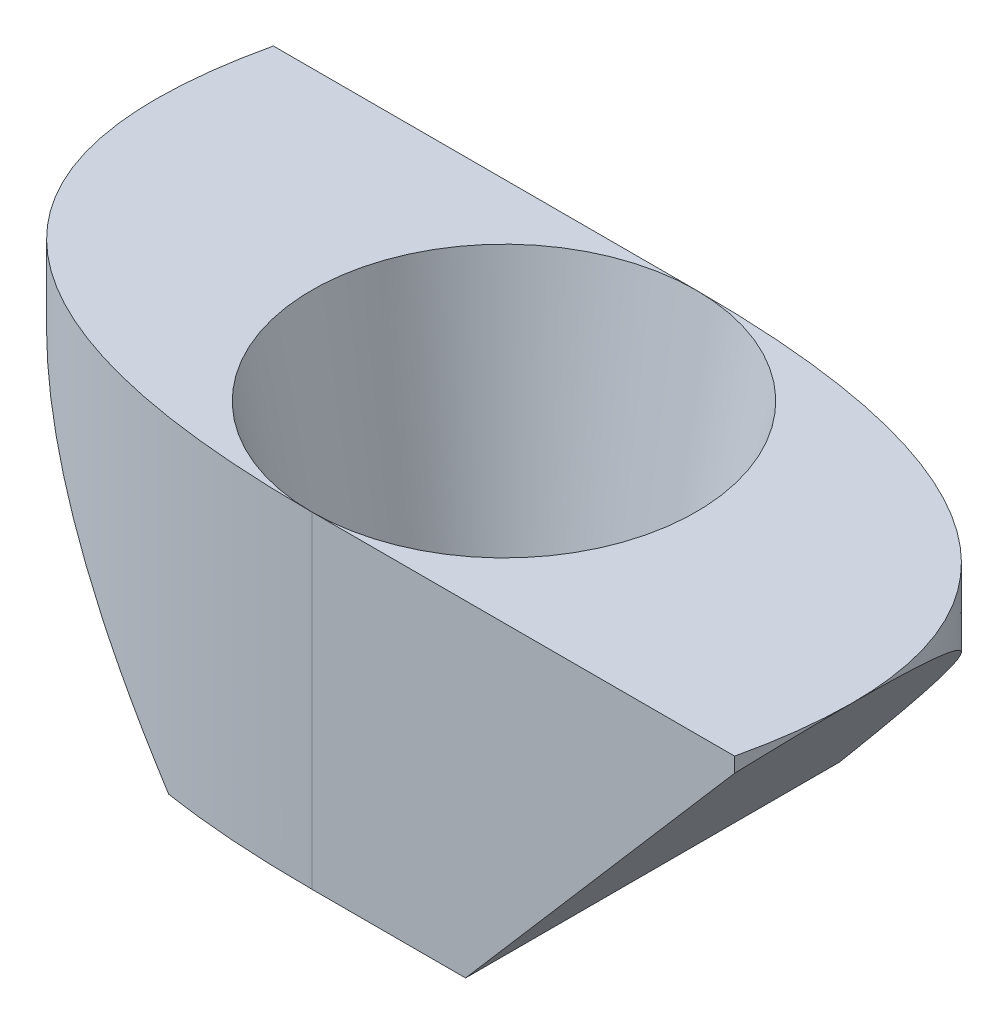
SolidWorks part; units mm, degrees
ref_plane "Front Plane" through (0, 0, 0) normal (0, 0, 1) x (1, 0, 0)
ref_plane "Top Plane" through (0, 0, 0) normal (0, 1, 0) x (1, 0, 0)
ref_plane "Right Plane" through (0, 0, 0) normal (1, 0, 0) x (0, 0, -1)
sketch "Sketch1" plane through (0, 0, 0) normal (0, 1, 0) x (1, 0, 0)
  line L0 (0, 3.175) -> (13.97, 3.175) construction
  line L1 (6.985, 0) -> (13.97, 0)
  line L3 (0, 6.35) -> (6.985, 6.35)
  line L5 (6.985, 6.35) -> (6.985, 0) construction
  spline S0 degree 2 poles (6.985, 6.35) (15.4152, 6.3545) (13.97, 0) knots 0 0 0 1 1 1
  spline S1 degree 2 poles (6.985, 0) (-1.4452, -0.0045) (0, 6.35) knots 0 0 0 1 1 1
  point P0 (6.985, 3.175)
extrude "Boss-Extrude2" add sketch "Sketch1" along normal blind 7.62 contours L3 S0 L1 S1
sketch "Sketch3" plane through (0, 0, 0) normal (0, 0, 1) x (1, 0, 0)
  line L1 (-0.2115, 7.62) -> (-0.2115, 0) construction
  line L3 (6.985, 7.62) -> (-0.2115, 7.62) construction
  line L4 (-0.2115, 7.62) -> (3.81, 7.62)
  line L9 (-0.2115, 7.62) -> (-0.2115, 5.461)
  line L10 (-0.2115, 7.62) -> (-0.2115, 5.461)
  spline S1 degree 2 poles (-4.2206, 5.1452) (-0.8562, 8.6762) (3.81, 7.62) knots 0 0 0 1 1 1
  spline S2 degree 2 poles (3.81, 7.62) (0.2921, 4.6891) (-4.2206, 5.1452) knots 0 0 0 1 1 1
  dimension "D1" = 4.0215
  dimension "D2" = 2.159
  dimension "D3" = 4.0215
sketch "Sketch9" plane through (0, 0, 0) normal (1, 0, 0) x (0, 0, -1)
  line L0 (0, 0) -> (0, 7.62)
sketch3d "3DSketch1"
  line L0 (3.4925, 7.62, -6.35) -> (3.4925, 8.6995, -6.35)
  line L1 (1.7993, 6.5405, 0) -> (3.4925, 8.6995, -6.35) construction
  line L2 (0, 7.62, -6.35) -> (6.985, 7.62, -6.35) construction
  line L3 (3.4925, 8.6995, -6.35) -> (6.9387, 8.6995, -6.35) construction
  line L5 (1.7993, 7.62, 0) -> (1.7993, 6.5405, 0) construction
  line L6 (-0.2115, 7.62, 0) -> (3.81, 7.62, 0) construction
  spline S0 degree 2 poles (1.7993, 6.5405, 0) (4.3297, 8.7967, -8.2995) (12.0803, 9.3942, -6.35) knots 0 0 0 1 1 1
  dimension "D1" = 1.0795
sketch "Sketch16" plane through (0, 0, 0) normal (0, -1, 0) x (1, 0, 0)
  line L1 (-0.6964, -6.7777) -> (14.6262, -6.7777)
  line L2 (-0.6964, -6.7777) -> (-0.6964, 0.5304)
  line L3 (-0.6964, 0.5304) -> (14.6262, 0.5304)
  line L4 (14.6262, -6.7777) -> (14.6262, 0.5304)
extrude "Cut-Extrude1" cut sketch "Sketch16" against normal blind 2.2225
sketch "Sketch17" plane through (0, 0, 0) normal (0, 0, 1) x (1, 0, 0)
  line L4 (6.985, 2.2225) -> (9.525, 2.2225) construction
  line L9 (6.985, 2.2225) -> (13.97, 2.2225) construction
  line L10 (9.525, 2.2225) -> (14.1815, 7.62)
  line L11 (14.1815, 7.62) -> (14.1815, 2.2225)
  line L12 (14.1815, 2.2225) -> (9.525, 2.2225)
  line L13 (6.985, 7.62) -> (6.985, 2.2225) construction
  line L14 (-0.2115, 2.2225) -> (4.445, 2.2225)
  line L15 (-0.2115, 7.62) -> (-0.2115, 2.2225)
  line L16 (4.445, 2.2225) -> (-0.2115, 7.62)
  dimension "D1" = 2.54
extrude "Cut-Extrude2" cut sketch "Sketch17" against normal up to surface (6.35 mm away) up to face at (3.4925, 4.9213, -6.35)
sketch "Sketch18" plane through (0, 7.62, 0) normal (0, 1, 0) x (1, 0, 0)
  line L0 (13.97, 0) -> (0, 6.35) construction
  circle A0 centre (6.985, 3.175) radius 3.175
extrude "Cut-Extrude3" cut sketch "Sketch18" against normal up to surface (5.3975 mm away) draft 10 contours A0
